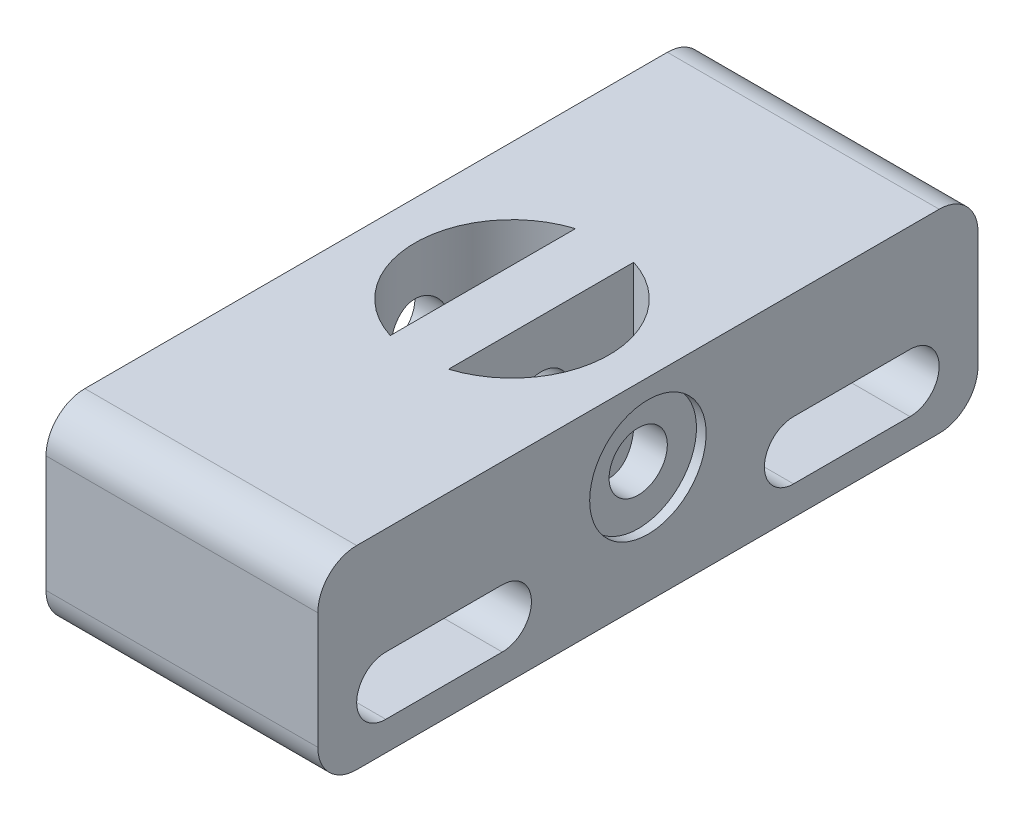
SolidWorks part; units mm, degrees
ref_plane "前视基准面" through (0, 0, 0) normal (0, 0, 1) x (1, 0, 0)
ref_plane "上视基准面" through (0, 0, 0) normal (0, 1, 0) x (1, 0, 0)
ref_plane "右视基准面" through (0, 0, 0) normal (1, 0, 0) x (0, 0, -1)
sketch "草图1" plane through (0, 0, 0) normal (0, 1, 0) x (1, 0, 0)
  line L0 (-10.0788, 0) -> (13.4422, 0) construction
  line L1 (-7, 17) -> (7, 17)
  line L2 (-7, 17) -> (-7, -17)
  line L3 (-7, -17) -> (7, -17)
  line L4 (7, 17) -> (7, -17)
  line L6 (-1.5, 4.7697) -> (-1.5, -4.7697)
  line L12 (1.5, 4.7697) -> (1.5, -4.7697)
  line L13 (0, 20.8509) -> (0, -19.4544) construction
  arc A2 (-1.5, 4.7697) -> (-1.5, -4.7697) centre (0, 0) ccw
  arc A3 (1.5, -4.7697) -> (1.5, 4.7697) centre (0, 0) ccw
  point P0 (0, 0)
  point P6 (0, 0)
  point P14 (7, 0)
  dimension "D1" = 14
  dimension "D2" = 34
extrude "凸台-拉伸1" add sketch "草图1" along normal blind 10
sketch "草图2" plane through (-7, 0, 0) normal (-1, 0, 0) x (0, 0, 1)
  line L0 (-17, 10) -> (17, 10) construction
  circle A0 centre (0, 6) radius 1.5
  dimension "D1" = 3
  dimension "D2" = 4
extrude "切除-拉伸1" cut sketch "草图2" against normal through all
sketch "草图3" plane through (-7, 0, 0) normal (-1, 0, 0) x (0, 0, 1)
  circle A0 centre (0, 6) radius 3
extrude "切除-拉伸2" cut sketch "草图3" against normal blind 0.5
mirror "镜向1" about plane through (0, 0, 0) normal (1, 0, 0) of "切除-拉伸2"
sketch "草图4" plane through (-7, 0, 0) normal (-1, 0, 0) x (0, 0, 1)
  line L0 (0, 12.5416) -> (0, -4.1511) construction
  line L1 (-13.5, 4.5) -> (-7.5, 4.5)
  line L2 (-7.5, 1.5) -> (-13.5, 1.5)
  line L3 (-17, 0) -> (17, 0) construction
  line L4 (-17, 10) -> (-17, 0) construction
  line L5 (7.5, 1.5) -> (13.5, 1.5)
  line L6 (13.5, 4.5) -> (7.5, 4.5)
  arc A0 (-13.5, 4.5) -> (-13.5, 1.5) centre (-13.5, 3) ccw
  arc A1 (-7.5, 1.5) -> (-7.5, 4.5) centre (-7.5, 3) ccw
  arc A2 (7.5, 1.5) -> (7.5, 4.5) centre (7.5, 3) cw
  arc A3 (13.5, 4.5) -> (13.5, 1.5) centre (13.5, 3) cw
  dimension "D1" = 1.5
  dimension "D2" = 3
  dimension "D3" = 3.5
  dimension "D4" = 6
extrude "切除-拉伸3" cut sketch "草图4" against normal through all
fillet "圆角1" radius 2 4 edges at (0, 10, 17) (0, 0, 17) (0, 0, -17) (0, 10, -17)
chamfer "倒角1" distance 0.6 angle 45 4 edges at (5, 0, 0) (1.5, 0, 0) (-1.5, 0, 0) (-5, 0, 0)
